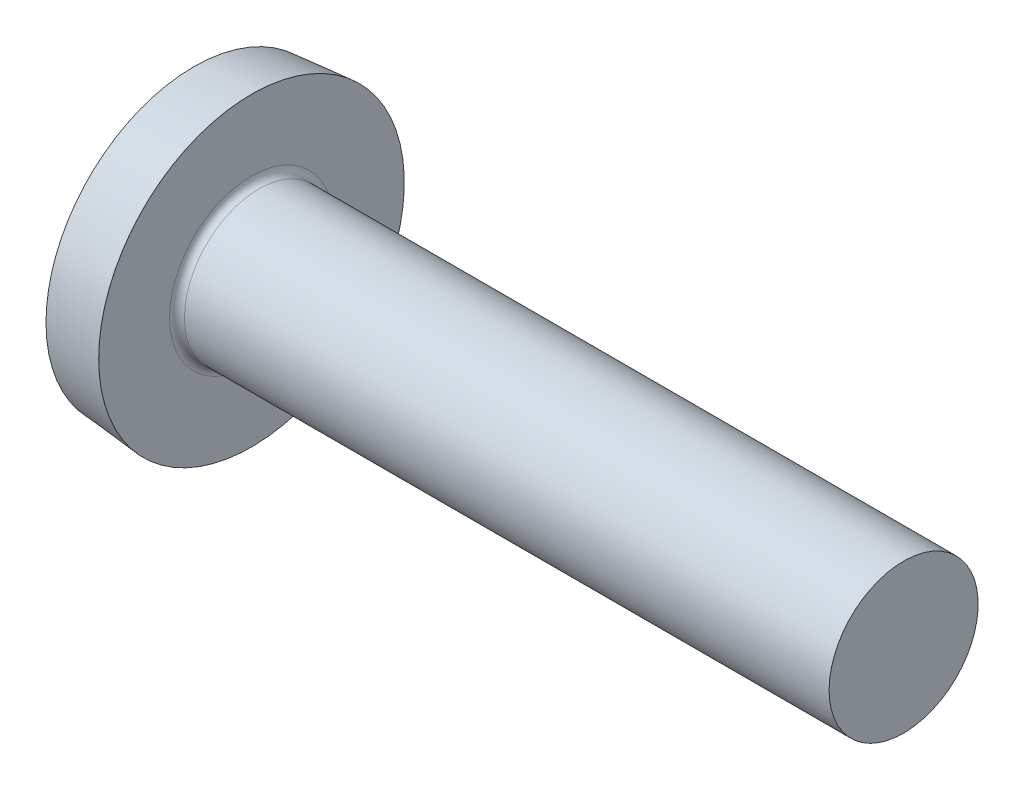
SolidWorks part; units mm, degrees
ref_plane "Plane1" through (0, 0, 0) normal (0, 0, 1) x (1, 0, 0)
ref_plane "Plane2" through (0, 0, 0) normal (0, 1, 0) x (1, 0, 0)
ref_plane "Plane3" through (0, 0, 0) normal (1, 0, 0) x (0, 0, -1)
sketch "BodySke" plane through (0, 0, 0) normal (0, 0, 1) x (1, 0, 0)
  line L0 (4.8, 4) -> (4.8, 8.2)
  line L1 (6.05, 6.35) -> (6.05, -3.175) construction
  line L2 (-25.4, 0) -> (127, 0) construction
  line L3 (39.8, 0) -> (0, 0)
  line L4 (4.8, 4) -> (39.8, 4)
  line L5 (39.8, 4) -> (39.8, 0)
  line L6 (1.7, 7.9297) -> (4.79, 8.2)
  line L8 (9.8, 6.35) -> (9.8, -3.175) construction
  line L9 (4.8, 8.2) -> (4.79, 8.2)
  arc A0 (1.7, 7.9297) -> (0, 0) centre (19.344, 0) ccw
  dimension "Length" = 35
  dimension "Head_ht" = 4.8
  dimension "Advance" = 1.25
  dimension "Thread_nom" = 30
  dimension "Diameter" = 8
  dimension "Head_dia" = 16.4
  dimension "Head_ang" = 85
  dimension "Oval_ht" = 1.7
  dimension "D1" = 0.01
revolve "Base-Revolve" add sketch "BodySke"
cosmetic thread "ThreadCosmetic" [suppressed]
fillet "Fillet1" radius 0.4 1 edges at (4.8, 0, 4)
sketch "Sketch3" plane through (0, 0, 0) normal (1, 0, 0) x (0, 0, -1)
  line L0 (0.71, -3.9) -> (-0.71, -3.9)
  line L1 (0.71, -3.9) -> (0.71, 3.9)
  line L2 (-0.71, 3.9) -> (0.71, 3.9)
  line L3 (-0.71, 3.9) -> (-0.71, -3.9)
  dimension "Cross_dia" = 7.8
  dimension "D1" = 3.9
  dimension "Cross_width" = 1.42
  dimension "D2" = 0.71
ref_plane "Plane4" through (4.36, 0, 0) normal (1, 0, 0) x (0, 0, -1)
sketch "Sketch4" plane through (4.36, 0, 0) normal (1, 0, 0) x (0, 0, -1)
  line L0 (0.71, -1.7262) -> (-0.71, -1.7262)
  line L1 (0.71, -1.7262) -> (0.71, 1.7262)
  line L2 (-0.71, 1.7262) -> (0.71, 1.7262)
  line L3 (-0.71, 1.7262) -> (-0.71, -1.7262)
  dimension "D1" = 1.42
  dimension "D2" = 3.4524
  dimension "D3" = 0.71
  dimension "D4" = 1.7262
loft "Recess" cut profiles "Sketch3", "Sketch4"
pattern_circular "RecPat" count 2 every 90 about axis through (0, 0, 0) along (1, 0, 0) of "Recess"
sketch "RecCorSke" plane through (0, 0, 0) normal (0, 0, 1) x (1, 0, 0)
  line L0 (-3.175, 0) -> (15.875, 0) construction
  line L1 (-25.4, 0) -> (127, 0) construction
  line L2 (0, 0) -> (0, 1.5854)
  line L3 (0, 1.5854) -> (4.36, 1.2805)
  line L4 (4.36, 1.2805) -> (4.7761, 0)
  line L5 (4.7761, 0) -> (0, 0)
  dimension "Diameter" = 2.561
  dimension "Depth" = 4.36
  dimension "Draft_angle" = 4
  dimension "Bottom_angle" = 18
revolve "RecessCore" cut sketch "RecCorSke" angle 360 about L0
sketch "ThdSchSke" plane through (0, 0, 0) normal (0, 0, 1) x (1, 0, 0)
  line L0 (9.8, -3.3095) -> (9.3165, -4)
  line L1 (9.8, -3.3095) -> (10.2835, -4)
  line L2 (10.2835, -4) -> (10.2835, -5)
  line L3 (-3.175, 0) -> (5.1513, 0) construction
  line L5 (10.2835, -5) -> (9.3165, -5)
  line L6 (9.3165, -5) -> (9.3165, -4)
  dimension "Diameter" = 8
  dimension "SideAngle" = 55
  dimension "VeeAngle" = 70
  dimension "Thread_minor" = 6.619
  dimension "Overcut" = 10
  dimension "Start" = 9.8
revolve "ThreadSchematic" [suppressed] cut sketch "ThdSchSke" angle 360 about L3
pattern_linear "ThdSchPat" [suppressed]
equation "' \"Diameter@BodySke\" = 8"
equation "' \"Length@BodySke\" = 35"
equation "' \"Head_dia@BodySke\" = 16.4"
equation "' \"Oval_ht@BodySke\" = 1.7"
equation "' \"Head_ht@BodySke\" = 4.8"
equation "' \"Thread_nom@BodySke\" =  30"
equation "' \"Thread_nom@BodySke\" = 30"
equation "' \"Head_ang@BodySke\" = 85"
equation "' \"Cross_dia@Sketch3\" = 7.8"
equation "' \"Cross_width@Sketch3\" = 1.42"
equation "' \"Cross_depth@Plane4\" = 4.36"
equation "' \"Diameter@RecCorSke\" = 2.561"
equation "' \"Radius@Fillet1\" = 0.4"
equation "' \"Thread_minor@ThreadCosmetic\" = 6.619"
equation "' \"Advance@BodySke\" = 1.25"
equation "\"D1@Sketch3\" = \"Cross_dia@Sketch3\" / 2"
equation "\"D2@Sketch3\" = \"Cross_width@Sketch3\" / 2"
equation "\"Depth@RecCorSke\" = \"Cross_depth@Plane4\""
equation "\"D1@Sketch4\" = \"Cross_width@Sketch3\""
equation "\"D2@Sketch4\" = \"Cross_dia@Sketch3\" - 2.0 * \"Cross_depth@Plane4\" * tan(26.5  * 0.017453292)"
equation "\"D3@Sketch4\" = \"D1@Sketch4\" / 2"
equation "\"D4@Sketch4\" = \"D2@Sketch4\" / 2"
equation "\"Thread_length@ThreadCosmetic\" = ((sgn( (\"Length@BodySke\" - \"Advance@BodySke\" * 2.0 ) - \"Thread_nom@BodySke\" )-1)*( (\"Length@BodySke\" - \"Advance@BodySke\" * 2.0 ) - \"Thread_nom@BodySke\" ))/-2+ \"Thread_nom@BodySke\""
equation "\"Thread_minor@ThdSchSke\" = \"Thread_minor@ThreadCosmetic\""
equation "\"Diameter@ThdSchSke\" = \"Diameter@BodySke\""
equation "\"Overcut@ThdSchSke\" = \"Diameter@BodySke\" * 1.25"
equation "\"Start@ThdSchSke\" = \"Head_ht@BodySke\" + \"Length@BodySke\" - \"Thread_length@ThreadCosmetic\"  '---Non-countersunk---"
equation "\"Num_threads@ThdSchPat\" = int( \"Thread_length@ThreadCosmetic\" / \"Advance@BodySke\" + 0.999 )  + 1"
equation "\"Advance@ThdSchPat\" = \"Thread_length@ThreadCosmetic\" /  (\"Num_threads@ThdSchPat\" - 1) 'relax it"
